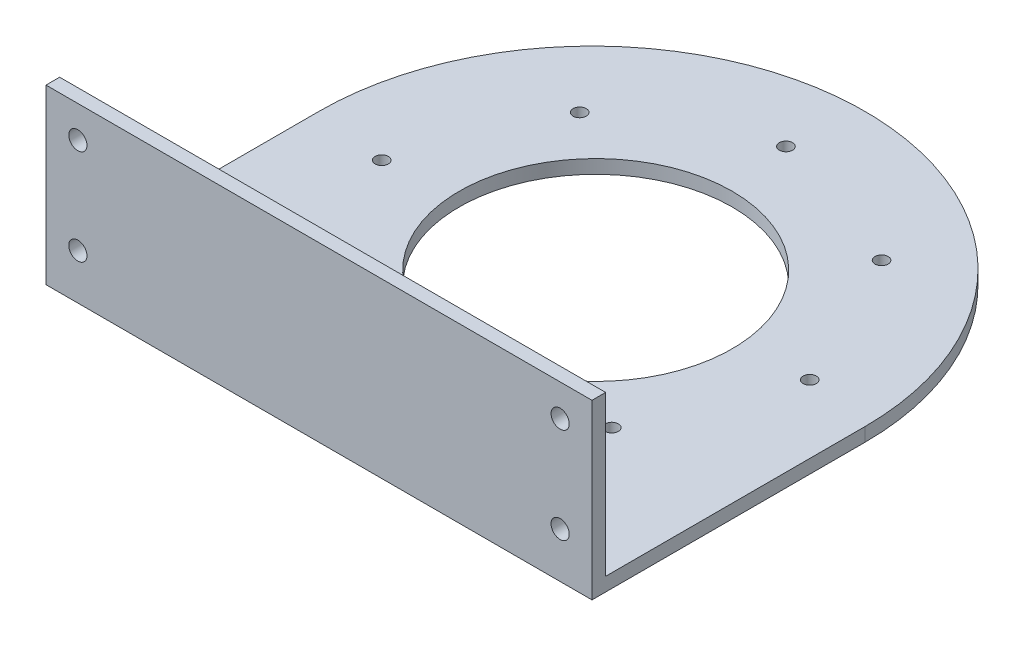
SolidWorks part; units mm, degrees
ref_plane "Front Plane" through (0, 0, 0) normal (0, 0, 1) x (1, 0, 0)
ref_plane "Top Plane" through (0, 0, 0) normal (0, 1, 0) x (1, 0, 0)
ref_plane "Right Plane" through (0, 0, 0) normal (1, 0, 0) x (0, 0, -1)
sketch "Sketch1" plane through (0, 0, 0) normal (0, 1, 0) x (1, 0, 0)
  line L0 (-60, 0) -> (-60, -60)
  line L1 (60, 0) -> (60, -60)
  line L2 (-60, -60) -> (60, -60)
  arc A17 (60, 0) -> (-60, 0) centre (0, 0) ccw
  arc A50 (-27.8614, -9.2442) -> (29.083, 9.6591) centre (0.6108, 0.2074) ccw
  arc A51 (29.083, 9.6591) -> (-27.8614, -9.2442) centre (0.6108, 0.2074) ccw
  arc A52 (45.1192, 1.3713) -> (44.949, 4.2663) centre (45.0341, 2.8188) ccw
  arc A53 (44.949, 4.2663) -> (45.1192, 1.3713) centre (45.0341, 2.8188) ccw
  arc A54 (32.4596, -29.4768) -> (32.2895, -26.5818) centre (32.3746, -28.0293) ccw
  arc A55 (32.2895, -26.5818) -> (32.4596, -29.4768) centre (32.3746, -28.0293) ccw
  arc A56 (3.3072, -45.6634) -> (3.1371, -42.7684) centre (3.2221, -44.2159) ccw
  arc A57 (3.1371, -42.7684) -> (3.3072, -45.6634) centre (3.2221, -44.2159) ccw
  arc A58 (-29.0398, -31.6036) -> (-28.8696, -34.4986) centre (-28.9547, -33.0511) ccw
  arc A59 (-28.8696, -34.4986) -> (-29.0398, -31.6036) centre (-28.9547, -33.0511) ccw
  arc A60 (-43.8976, -0.9564) -> (-43.7274, -3.8514) centre (-43.8125, -2.4039) ccw
  arc A61 (-43.7274, -3.8514) -> (-43.8976, -0.9564) centre (-43.8125, -2.4039) ccw
  arc A62 (-31.2381, 29.8917) -> (-31.0679, 26.9967) centre (-31.153, 28.4442) ccw
  arc A63 (-31.0679, 26.9967) -> (-31.2381, 29.8917) centre (-31.153, 28.4442) ccw
  arc A64 (-1.9155, 43.1832) -> (-2.0857, 46.0782) centre (-2.0006, 44.6307) ccw
  arc A65 (-2.0857, 46.0782) -> (-1.9155, 43.1832) centre (-2.0006, 44.6307) ccw
  arc A66 (30.0912, 34.9135) -> (30.2614, 32.0185) centre (30.1763, 33.466) ccw
  arc A67 (30.2614, 32.0185) -> (30.0912, 34.9135) centre (30.1763, 33.466) ccw
  dimension "D1" = 30
  dimension "D2" = 120
  dimension "D3" = 60
  dimension "D4" = 60
extrude "Boss-Extrude1" add sketch "Sketch1" along normal blind 3
sketch "Sketch2" plane through (-60, 0, 0) normal (-1, 0, 0) x (0, 0, 1)
  line L0 (60, 3) -> (60, 38)
  line L1 (60, 38) -> (57, 38)
  line L2 (57, 38) -> (57, 3)
  line L3 (0, 3) -> (60, 3) construction
  line L8 (0, 0) -> (60, 0)
  line L9 (60, 0) -> (60, 3)
  line L10 (60, 3) -> (0, 3)
  line L11 (0, 3) -> (0, 0)
  line L14 (60, 3) -> (57, 3)
  dimension "D1" = 3
  dimension "D2" = 35
  dimension "D3" = 0
extrude "Boss-Extrude2" add sketch "Sketch2" along direction (1, 0, 0) on the side against the normal blind 120
sketch "Sketch3" plane through (0, 0, 57) normal (0, 0, -1) x (-1, 0, 0)
  line L0 (-60, 38) -> (60, 38) construction
  line L1 (-60, 38) -> (-60, 3) construction
  line L2 (-60, 20.5) -> (60, 20.5) construction
  line L3 (60, 38) -> (60, 3) construction
  circle A0 centre (-53, 31) radius 2
  circle A1 centre (53, 31) radius 2
  circle A2 centre (53, 10) radius 2
  circle A3 centre (-53, 10) radius 2
  dimension "D1" = 4
  dimension "D2" = 7
  dimension "D3" = 7
extrude "Cut-Extrude1" cut sketch "Sketch3" against normal blind 10
